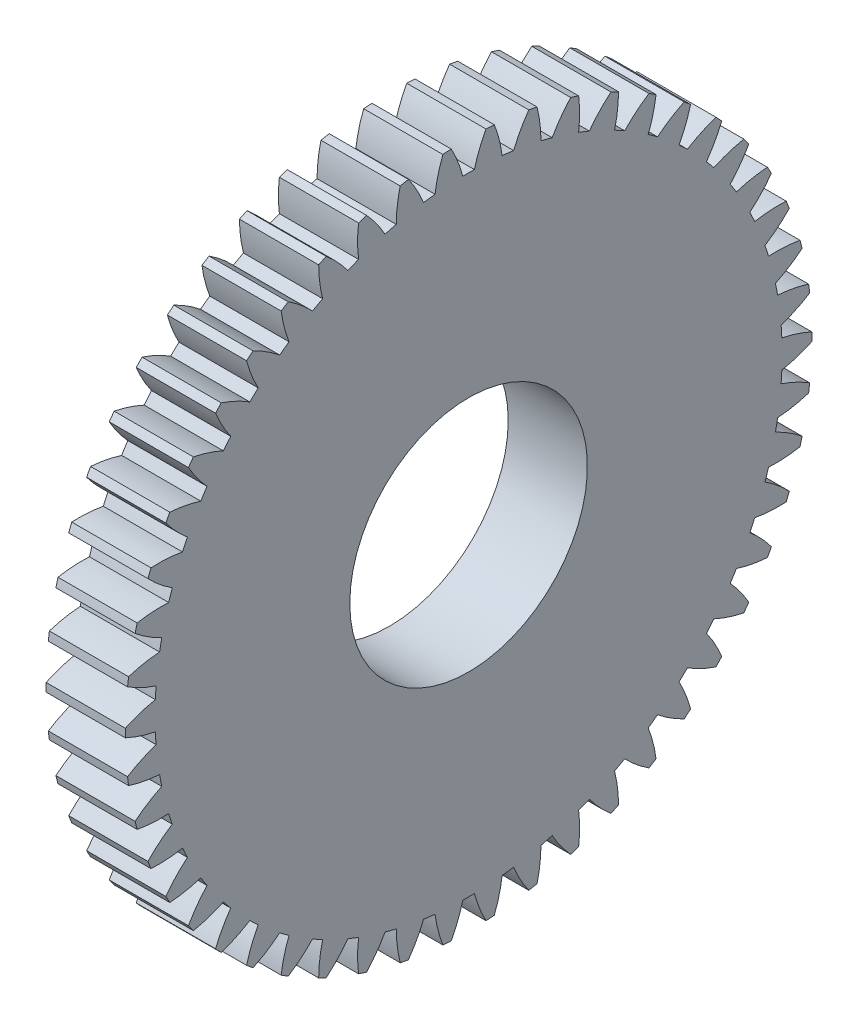
SolidWorks part; units mm, degrees
ref_plane "Plane1" through (0, 0, 0) normal (0, 0, 1) x (1, 0, 0)
ref_plane "Plane2" through (0, 0, 0) normal (0, 1, 0) x (1, 0, 0)
ref_plane "Plane3" through (0, 0, 0) normal (1, 0, 0) x (0, 0, -1)
sketch "HoldingSke" plane through (0, 0, 0) normal (0, 1, 0) x (1, 0, 0)
  line L0 (0, 0) -> (1.2856, -1.5321)
  line L1 (-15, 0) -> (100, 0) construction
  line L2 (0, 0) -> (-2.1039, 2.3779)
  line L3 (0, 0) -> (-11.863, 4.5341)
  line L4 (0, 0) -> (5.5511, 6.6156)
  line L5 (0, 0) -> (-46.8476, -17.4728)
  line L6 (0, 0) -> (-2.4869, -1.6779)
  line L7 (-2.1039, 2.3779) -> (8.6586, 51.2059)
  line L8 (-76.2, 54.61) -> (-74.8, 54.61)
  line L9 (-71.009, 38.7566) -> (-53.1078, 45.2721)
  line L10 (-76.2, 71.12) -> (104.1128, 71.12)
  line L11 (0, 0) -> (-3, 0)
  line L12 (-76.2, 101.6) -> (-76.181, 101.6)
  line L13 (24.9733, 27.94) -> (52.9518, 28.4284)
  line L14 (24.9733, 27.94) -> (24.9743, 27.94)
  line L15 (24.9733, 27.94) -> (100.4006, 29.5858)
  line L16 (-63.627, -0.5) -> (-12.827, -0.5)
  circle A0 centre (0, 0) radius 4.5
  circle A1 centre (0, 0) radius 11.874
  circle A2 centre (0, 0) radius 37.5
  circle A3 centre (0, 0) radius 4.5
  dimension "MHD" = 23.748
  dimension "Hub_dia" = 75
  dimension "Bore" = 9
  dimension "MBD" = 9
  dimension "Num_teeth" = 50
  dimension "Pitch" = 2
  dimension "Overall_len" = 50
  dimension "Show_teeth" = 50
  dimension "Thickness" = 3
  dimension "OAL" = 50.0001
  dimension "T_dim" = 1.4
  dimension "Ap" = 20
  dimension "H" = 19.05
  dimension "Pitch_radius" = 180.3128
  dimension "Width" = 3
  dimension "Backlash" = 0.019
  dimension "Addendum_fac" = 1
  dimension "Dedendum_fac" = 1.25
  dimension "Clearance_fac" = 0.25
  dimension "Dedendum_add" = 0.001
  dimension "Module" = 0.5
sketch "BasProSke" plane through (0, 0, 0) normal (0, 1, 0) x (1, 0, 0)
  line L0 (-10, 0) -> (60, 0) construction
  line L1 (0, 0) -> (0, 13)
  line L2 (0, 0) -> (3, 0)
  line L3 (3, 0) -> (3, 13)
  line L4 (3, 13) -> (0, 13)
  dimension "Thickness" = 3
  dimension "Diameter" = 26
revolve "Base-Revolve" add sketch "BasProSke" angle 360 about L0
sketch "TooCutSke" plane through (0, 0, 0) normal (1, 0, 0) x (0, 0, -1)
  line L1 (0, 0) -> (0, 107) construction
  line L2 (0, 0) -> (-0.4259, 12.4927) construction
  line L3 (0, 0) -> (-1.5691, 24.9404) construction
  line L4 (-0.4259, 12.4927) -> (-0.7846, 12.4702) construction
  arc A0 (0.2187, 11.872) -> (-0.2187, 11.872) centre (0, 0) ccw
  arc A1 (0.6715, 13.0081) -> (-0.6715, 13.0081) centre (0, 0) ccw
  circle A2 centre (0, 0) radius 12.5 construction
  circle A3 centre (0, 0) radius 11.7462 construction
  arc A4 (-0.2187, 11.872) -> (-0.6715, 13.0081) centre (-5.0549, 10.6028) ccw
  arc A5 (0.6715, 13.0081) -> (0.2187, 11.872) centre (5.0549, 10.6028) ccw
  dimension "Root_dia" = 23.748
  dimension "Overcut_dia" = 26.0508
  dimension "Pitch_dia" = 25
  dimension "Base_dia" = 23.4923
  dimension "Flank_rad" = 5
  dimension "Half_ang" = 3.6
  dimension "Half_CT" = 0.3594
extrude "ToothCut" cut sketch "TooCutSke" along normal through all
fillet "Breaks" [suppressed] radius 0.01
fillet "RootFillets" [suppressed] radius 0.126
pattern_circular "TeethCuts" count 50 every 7.2 about axis through (-10, 0, 0) along (1, 0, 0) of "ToothCut", "RootFillets", "Breaks"
sketch "HubNeaOneSke" plane through (0, 0, 0) normal (-1, 0, 0) x (0, 0, 1)
  circle A0 centre (0, 0) radius 11.874
  dimension "Diameter" = 23.748
extrude "HubNearOne" [suppressed] add sketch "HubNeaOneSke" along normal blind 47.0001
sketch "HubNeaBotSke" plane through (0, 0, 0) normal (-1, 0, 0) x (0, 0, 1)
  circle A0 centre (0, 0) radius 11.874
  dimension "Diameter" = 23.748
extrude "HubNearBoth" [suppressed] add sketch "HubNeaBotSke" along normal blind 23.5
ref_plane "FarPln" through (3, 0, 0) normal (1, 0, 0) x (0, 0, -1)
sketch "HubFarSke" plane through (3, 0, 0) normal (1, 0, 0) x (0, 0, -1)
  circle A0 centre (0, 0) radius 11.874
  dimension "Diameter" = 23.748
extrude "HubFar" [suppressed] add sketch "HubFarSke" along normal blind 23.5
sketch "BorSke" plane through (0, 0, 0) normal (1, 0, 0) x (0, 0, -1)
  circle A0 centre (0, 0) radius 4.5
  dimension "Diameter" = 9
extrude "Bore" cut sketch "BorSke" along normal mid plane 100.0001
sketch "KeySke" plane through (0, 0, 0) normal (1, 0, 0) x (0, 0, -1)
  line L0 (-1.5, 0) -> (-1.5, 5.9)
  line L1 (-1.5, 5.9) -> (1.5, 5.9)
  line L2 (1.5, 5.9) -> (1.5, 0)
  line L3 (0, 0) -> (0, 34) construction
  line L4 (-1.5, 0) -> (1.5, 0)
  dimension "Width" = 3
  dimension "Offset" = 5.9
extrude "Keyway" [suppressed] cut sketch "KeySke" along normal mid plane 100.0001
pattern_circular "Keyway2" [suppressed] count 2 every 90 about axis through (-10, 0, 0) along (1, 0, 0)
equation "' \"Module@HoldingSke\" = 6.35"
equation "' \"Num_teeth@HoldingSke\" = 12"
equation "' \"Ap@HoldingSke\" =  20"
equation "' \"Ap@HoldingSke\" = 20"
equation "' \"Width@HoldingSke\" = 0.5 * 25.4"
equation "' \"Hub_dia@HoldingSke\"= 1 * 25.4"
equation "' \"Hub_dia@HoldingSke\" = 1 * 25.4"
equation "' \"Overall_len@HoldingSke\" = 1.0 * 25.4"
equation "' \"Bore@HoldingSke\" = 0.75 * 25.4"
equation "' \"T_dim@HoldingSke\" = 0.1 * 25.4"
equation "' \"Width@KeySke\" = 0.25 * 25.4"
equation "' \"Show_teeth@HoldingSke\" = 13"
equation "' \"Backlash@HoldingSke\" = 0.009 * 25.4"
equation "' \"Addendum_fac@HoldingSke\" = 1.0"
equation "' \"Dedendum_fac@HoldingSke\" = 1.25"
equation "' \"Dedendum_add@HoldingSke\" = 0.00005 * 25.4"
equation "' \"Clearance_fac@HoldingSke\" = 0.25"
equation "\"Pitch@HoldingSke\" = 1 / \"Module@HoldingSke\""
equation "\"Overcut_dia@TooCutSke\" = (\"Num_teeth@HoldingSke\" + 2 * \"Addendum_fac@HoldingSke\") / \"Pitch@HoldingSke\" + 0.002 * 25.4"
equation "\"Pitch_dia@TooCutSke\" = \"Num_teeth@HoldingSke\" / \"Pitch@HoldingSke\""
equation "\"Base_dia@TooCutSke\" = \"Num_teeth@HoldingSke\" / \"Pitch@HoldingSke\" * cos((\"Ap@HoldingSke\"  * 3.14159265 / 180))"
equation "\"Root_dia@TooCutSke\" = (\"Num_teeth@HoldingSke\" + 2) / \"Pitch@HoldingSke\" - 2 * (\"Addendum_fac@HoldingSke\" + \"Dedendum_fac@HoldingSke\") / \"Pitch@HoldingSke\" - \"Dedendum_add@HoldingSke\" * 2"
equation "\"Half_ang@TooCutSke\" = 180 / \"Num_teeth@HoldingSke\""
equation "\"Half_CT@TooCutSke\" = \"Num_teeth@HoldingSke\" / \"Pitch@HoldingSke\" * sin((3.14159265 / 2 / \"Num_teeth@HoldingSke\")) / 2 - 7 * \"Backlash@HoldingSke\" / 4"
equation "\"Flank_rad@TooCutSke\" = \"Num_teeth@HoldingSke\" / \"Pitch@HoldingSke\" / 5"
equation "\"Radius@RootFillets\" = \"Clearance_fac@HoldingSke\" / \"Pitch@HoldingSke\" + \"Dedendum_add@HoldingSke\""
equation "\"Break_rad@Breaks\" = 0.02 / \"Pitch@HoldingSke\""
equation "\"Thickness@HoldingSke\" = \"Width@HoldingSke\""
equation "\"OAL@HoldingSke\" = \"Thickness@HoldingSke\""
equation "\"MHD@HoldingSke\" = (\"Num_teeth@HoldingSke\" + 2) / \"Pitch@HoldingSke\" - 2 * (\"Addendum_fac@HoldingSke\" + \"Dedendum_fac@HoldingSke\")  / \"Pitch@HoldingSke\" - \"Dedendum_add@HoldingSke\" * 2"
equation "\"MBD@HoldingSke\" = (\"Num_teeth@HoldingSke\" + 2) / \"Pitch@HoldingSke\" - 2 * (\"Addendum_fac@HoldingSke\" + \"Dedendum_fac@HoldingSke\")  / \"Pitch@HoldingSke\" - \"Dedendum_add@HoldingSke\" * 2 - 0.002 * 25.4"
equation "\"MHD@HoldingSke\" = ((sgn( \"MHD@HoldingSke\" - \"Hub_dia@HoldingSke\" )-1)*( \"MHD@HoldingSke\" - \"Hub_dia@HoldingSke\" ))/-2+ \"Hub_dia@HoldingSke\""
equation "\"MBD@HoldingSke\" = ((sgn( \"MBD@HoldingSke\" - \"Bore@HoldingSke\" )-1)*( \"MBD@HoldingSke\" - \"Bore@HoldingSke\" ))/-2+ \"Bore@HoldingSke\""
equation "\"OAL@HoldingSke\" = ((sgn( \"OAL@HoldingSke\" - \"Overall_len@HoldingSke\" )+1)*( \"OAL@HoldingSke\" - \"Overall_len@HoldingSke\" ))/2 + \"Overall_len@HoldingSke\" + 0.000002 * 25.4"
equation "\"Num_teeth@TeethCuts\" = int( \"Show_teeth@HoldingSke\" ) + 1"
equation "\"Num_teeth@TeethCuts\" = ((sgn( \"Num_teeth@TeethCuts\" - \"Num_teeth@HoldingSke\" )-1)*( \"Num_teeth@TeethCuts\" - \"Num_teeth@HoldingSke\" ))/-2+ \"Num_teeth@HoldingSke\""
equation "\"Num_teeth@TeethCuts\" = ((sgn( \"Num_teeth@TeethCuts\" - 2.0)+1)*( \"Num_teeth@TeethCuts\" - 2.0))/2 +2.0"
equation "\"Angle@TeethCuts\" = 360.0 / \"Num_teeth@HoldingSke\""
equation "\"Diameter@BasProSke\" = (\"Num_teeth@HoldingSke\" + 2 * \"Addendum_fac@HoldingSke\") / \"Pitch@HoldingSke\""
equation "\"Thickness@BasProSke\"  = \"Thickness@HoldingSke\""
equation "' \"Fillet_rad@BasProSke\" =  \"Thickness@HoldingSke\" * 0.05"
equation "' \"Fillet_rad@BasProSke\" = \"Thickness@HoldingSke\" * 0.05"
equation "\"MHD@HoldingSke\" = ((sgn( \"MHD@HoldingSke\" - \"Root_dia@TooCutSke\" )-1)*( \"MHD@HoldingSke\" - \"Root_dia@TooCutSke\" ))/-2+ \"Root_dia@TooCutSke\""
equation "\"Diameter@HubNeaOneSke\" = \"MHD@HoldingSke\""
equation "\"Length@HubNearOne\" = \"OAL@HoldingSke\" - \"Thickness@BasProSke\""
equation "\"Diameter@HubNeaBotSke\" = \"MHD@HoldingSke\""
equation "\"Length@HubNearBoth\" = ( \"OAL@HoldingSke\" - \"Thickness@BasProSke\" ) / 2.0"
equation "\"Thickness@FarPln\" = \"Thickness@BasProSke\""
equation "\"Diameter@HubFarSke\" = \"MHD@HoldingSke\""
equation "\"Length@HubFar\" = ( \"OAL@HoldingSke\" - \"Thickness@BasProSke\" ) / 2.0"
equation "\"Diameter@BorSke\" = \"MBD@HoldingSke\""
equation "\"D1@Bore\" = \"OAL@HoldingSke\" * 2.0"
equation "\"D1@Keyway\" = \"OAL@HoldingSke\" * 2.0"
equation "\"Offset@KeySke\" = \"T_dim@HoldingSke\" + \"MBD@HoldingSke\" / 2.0"
